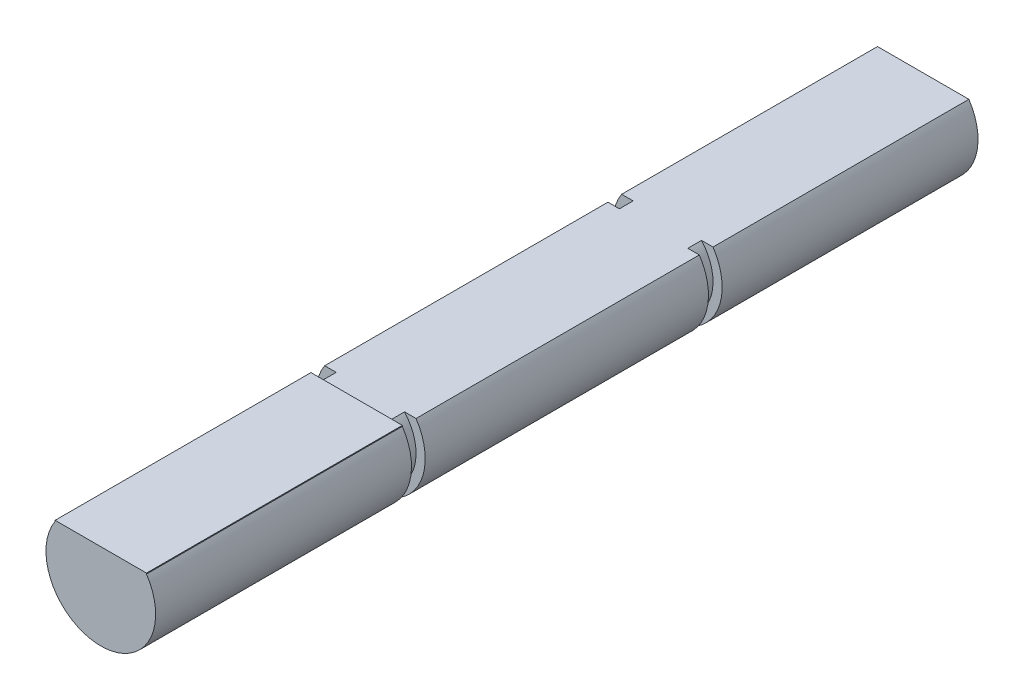
SolidWorks part; units mm, degrees
material "AISI 1020"
ref_plane "Спереди" through (0, 0, 0) normal (0, 0, 1) x (1, 0, 0)
ref_plane "Сверху" through (0, 0, 0) normal (0, 1, 0) x (1, 0, 0)
ref_plane "Справа" through (0, 0, 0) normal (1, 0, 0) x (0, 0, -1)
sketch "Эскиз1" plane through (0, 0, 0) normal (0, 0, 1) x (1, 0, 0)
  line L1 (-5, 3.3166) -> (5, 3.3166)
  arc A0 (-5, 3.3166) -> (5, 3.3166) centre (0, 0) ccw
  dimension "D1" = 12
  dimension "D2" = 10
extrude "Бобышка-Вытянуть1" add sketch "Эскиз1" along normal blind 45
sketch "Эскиз2" plane through (0, 0, 0) normal (0, 1, 0) x (1, 0, 0)
  line L0 (0, -1000) -> (0, 49000) construction
  line L1 (5, -15.5) -> (6, -15.5)
  line L2 (5, -15.5) -> (5, -17)
  line L3 (5, -17) -> (6, -17)
  line L4 (6, -15.5) -> (6, -17)
  line L7 (6, -45) -> (6, 0) construction
  line L8 (5, 0) -> (-5, 0) construction
  dimension "D1" = 1
  dimension "D2" = 1.5
  dimension "D3" = 17
revolve "Вырез-Повернуть1" cut sketch "Эскиз2" angle 360 about L0
mirror "Зеркальное отражение1" about plane through (0, 0, 0) normal (0, 0, 1) of bodies 104
sketch "Эскиз3" plane through (0, 3.3166, 0) normal (0, 1, 0) x (1, 0, 0)
  line L1 (-5, -45) -> (5, -45)
  line L2 (-5, -45) -> (-5, -17)
  line L3 (-5, -17) -> (5, -17)
  line L4 (5, -45) -> (5, -17)
  line L5 (5, -45) -> (5, -17) construction
  line L6 (5, -17) -> (3.7417, -17) construction
  line L7 (-5, -45) -> (-5, -17) construction
  point P6 (-2.794, -18.6353)
  point P7 (0, 0)
  point P9 (0, 0)
  point P13 (0, 0)
  point P16 (0, 0)
extrude "Бобышка-Вытянуть2" add sketch "Эскиз3" along normal blind 0.1
